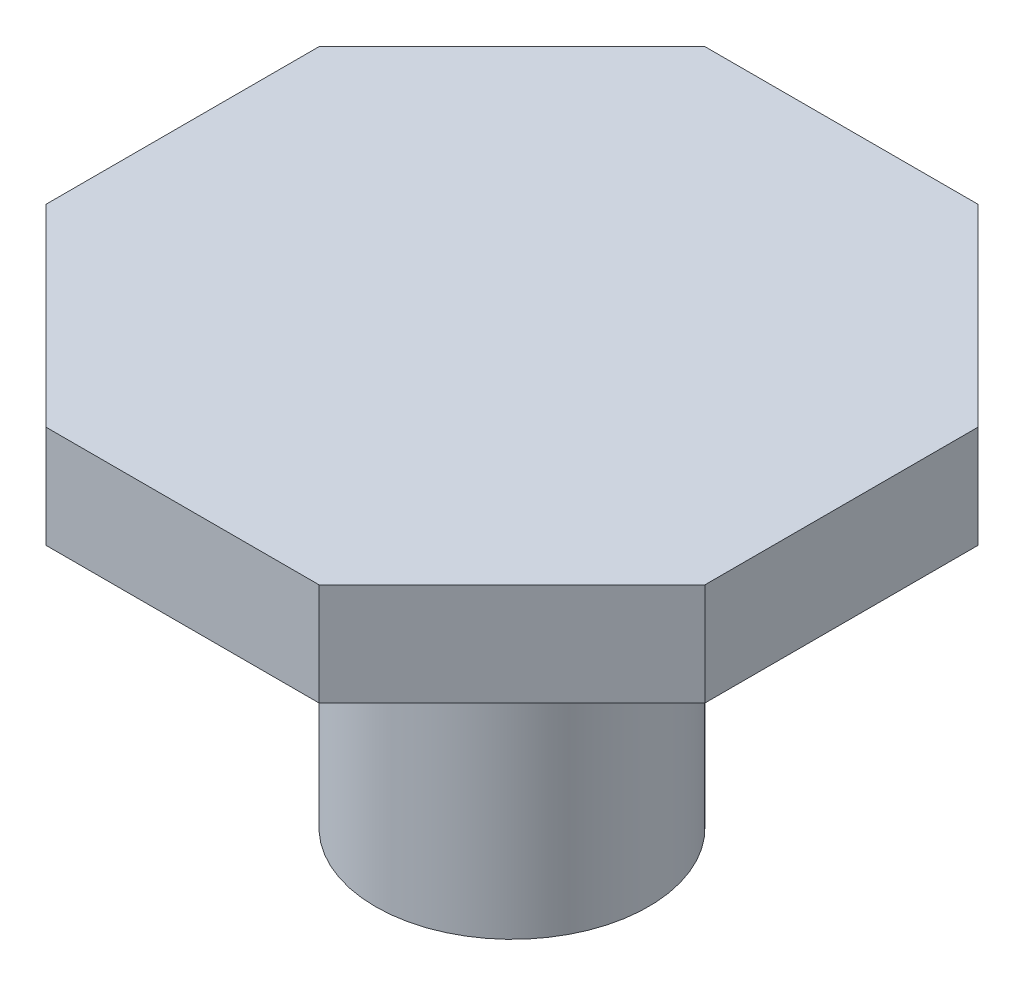
SolidWorks part; units mm, degrees
ref_plane "Front Plane" through (0, 0, 0) normal (0, 0, 1) x (1, 0, 0)
ref_plane "Top Plane" through (0, 0, 0) normal (0, 1, 0) x (1, 0, 0)
ref_plane "Right Plane" through (0, 0, 0) normal (1, 0, 0) x (0, 0, -1)
sketch "Sketch1" plane through (0, 0, 0) normal (0, 1, 0) x (1, 0, 0)
  circle A0 centre (0, 0) radius 2
  dimension "D1" = 4
extrude "Boss-Extrude1" add sketch "Sketch1" along normal blind 5
sketch "Sketch2" plane through (0, 5, 0) normal (0, 1, 0) x (1, 0, 0)
  line L1 (4.8284, 2) -> (2, 4.8284)
  line L2 (2, 4.8284) -> (-2, 4.8284)
  line L3 (-2, 4.8284) -> (-4.8284, 2)
  line L4 (-4.8284, 2) -> (-4.8284, -2)
  line L5 (-4.8284, -2) -> (-2, -4.8284)
  line L6 (-2, -4.8284) -> (2, -4.8284)
  line L7 (2, -4.8284) -> (4.8284, -2)
  line L8 (4.8284, -2) -> (4.8284, 2)
  circle A0 centre (0, 0) radius 4.8284 construction
  point P1 (0, 0)
  dimension "D1" = 4
extrude "Boss-Extrude2" add sketch "Sketch2" along normal blind 1.5
